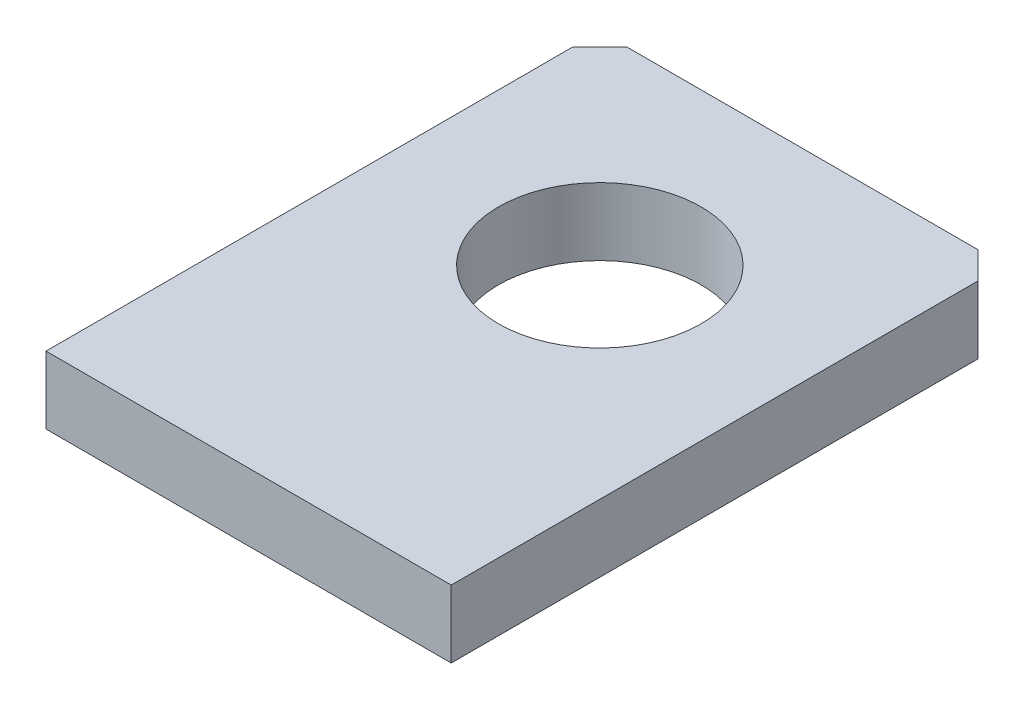
SolidWorks part; units mm, degrees
ref_plane "Alzado" through (0, 0, 0) normal (0, 0, 1) x (1, 0, 0)
ref_plane "Planta" through (0, 0, 0) normal (0, 1, 0) x (1, 0, 0)
ref_plane "Vista lateral" through (0, 0, 0) normal (1, 0, 0) x (0, 0, -1)
sketch "Croquis1" plane through (0, 0, 0) normal (0, 1, 0) x (1, 0, 0)
  line L1 (1.5, -2.05) -> (-1.5, -2.05)
  line L2 (1.5, -2.05) -> (1.5, 2.05)
  line L3 (1.5, 2.05) -> (-1.5, 2.05)
  line L4 (-1.5, -2.05) -> (-1.5, 2.05)
  line L5 (1.5, -2.05) -> (-1.5, 2.05) construction
  line L6 (1.5, 2.05) -> (-1.5, -2.05) construction
  point P0 (0, 0)
  dimension "D1" = 3
  dimension "D2" = 4.1
extrude "Saliente-Extruir1" add sketch "Croquis1" along normal blind 0.5
chamfer "Chaflán1" distance 0.2 angle 45 2 edges at (1.5, 0.25, -2.05) (-1.5, 0.25, -2.05)
sketch "Croquis2" plane through (0, 0.5, 0) normal (0, 1, 0) x (1, 0, 0)
  line L0 (1.3, 2.05) -> (-1.3, 2.05) construction
  circle A0 centre (0, 0.55) radius 0.75
  dimension "D1" = 1.5
  dimension "D2" = 1.5
extrude "Cortar-Extruir1" cut sketch "Croquis2" against normal blind 0.5
